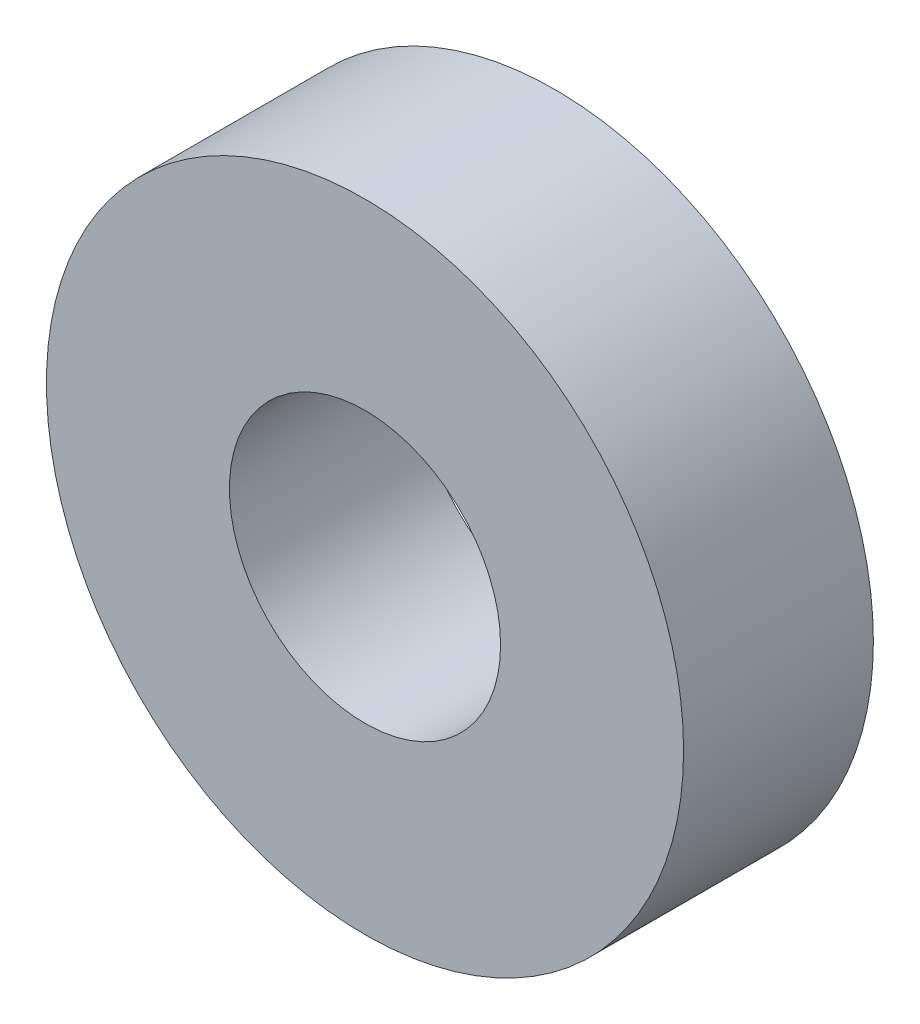
SolidWorks part; units mm, degrees
ref_plane "Front Plane" through (0, 0, 0) normal (0, 0, 1) x (1, 0, 0)
ref_plane "Top Plane" through (0, 0, 0) normal (0, 1, 0) x (1, 0, 0)
ref_plane "Right Plane" through (0, 0, 0) normal (1, 0, 0) x (0, 0, -1)
sketch "Sketch1" plane through (0, 0, 0) normal (0, 0, 1) x (1, 0, 0)
  circle A0 centre (0, 0) radius 10
  circle A1 centre (0, 0) radius 23.5
  dimension "D1" = 47
  dimension "D2" = 20
extrude "Boss-Extrude1" add sketch "Sketch1" along normal blind 14
